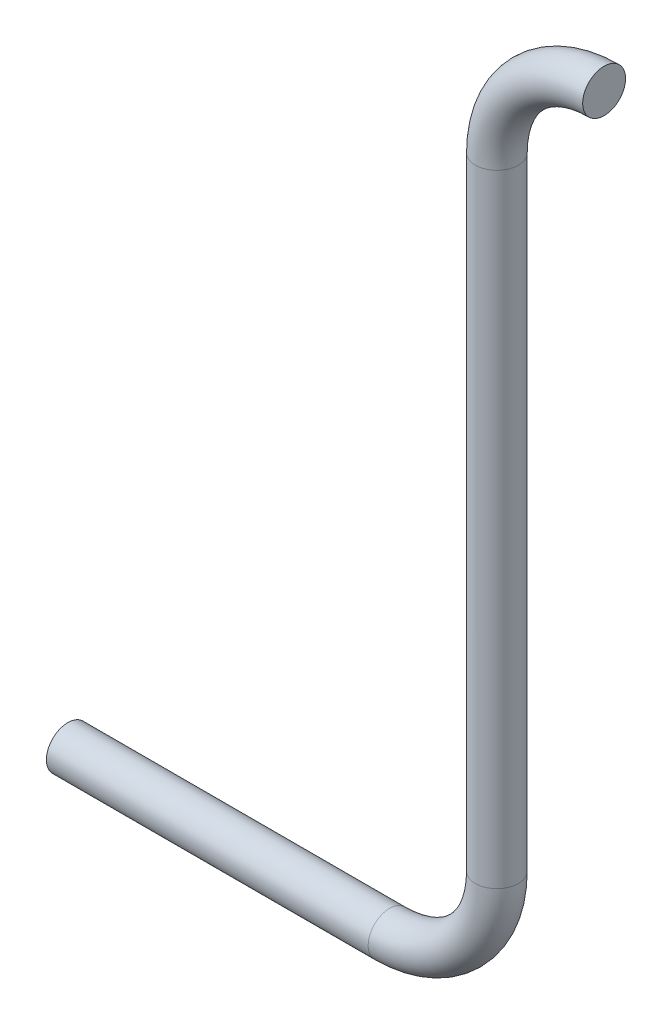
SolidWorks part; units mm, degrees
ref_plane "Спереди" through (0, 0, 0) normal (0, 0, 1) x (1, 0, 0)
ref_plane "Сверху" through (0, 0, 0) normal (0, 1, 0) x (1, 0, 0)
ref_plane "Справа" through (0, 0, 0) normal (1, 0, 0) x (0, 0, -1)
sketch "Эскиз1" plane through (0, 0, 0) normal (0, 0, 1) x (1, 0, 0)
  line L0 (-5, -5) -> (-5, -34)
  line L1 (-10, -39) -> (-25, -39)
  arc A0 (-5, -34) -> (-10, -39) centre (-10, -34) cw
  arc A1 (0, 0) -> (-5, -5) centre (0, -5) ccw
  dimension "D1" = 5
sketch "Эскиз2" plane through (0, 0, 0) normal (1, 0, 0) x (0, 0, -1)
  circle A0 centre (0, 0) radius 1
  dimension "D1" = 2
sweep "По траектории1" add profiles "Эскиз2" path "Эскиз1"
